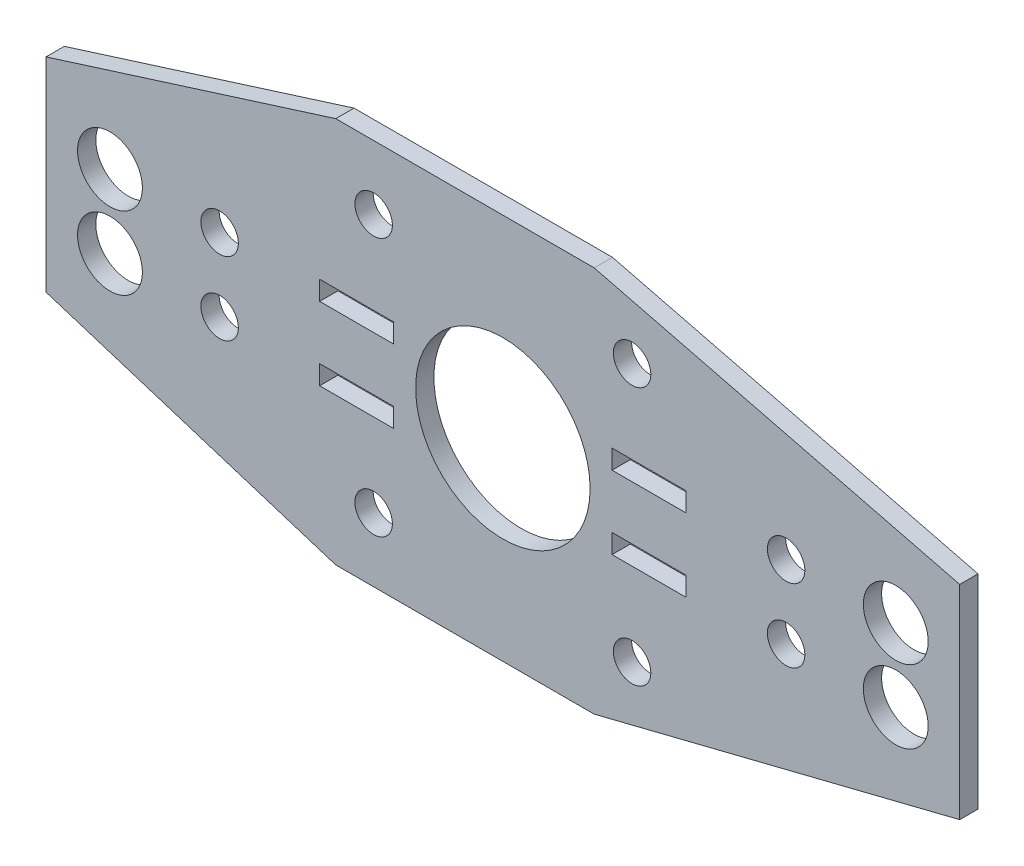
SolidWorks part; units mm, degrees
ref_plane "前视基准面" through (0, 0, 0) normal (0, 0, 1) x (1, 0, 0)
ref_plane "上视基准面" through (0, 0, 0) normal (0, 1, 0) x (1, 0, 0)
ref_plane "右视基准面" through (0, 0, 0) normal (1, 0, 0) x (0, 0, -1)
sketch "草图1" plane through (0, 0, 0) normal (0, 0, 1) x (1, 0, 0)
  line L0 (0, 0) -> (0, -8) construction
  line L1 (0, 0) -> (15, 0)
  line L2 (0, 0) -> (62, 0) construction
  line L3 (19.05, -1.05) -> (10.95, -1.05)
  line L4 (19.05, -1.05) -> (19.05, 1.05)
  line L5 (19.05, 1.05) -> (10.95, 1.05)
  line L6 (10.95, -1.05) -> (10.95, 1.05)
  line L7 (19.05, -1.05) -> (10.95, 1.05) construction
  line L8 (19.05, 1.05) -> (10.95, -1.05) construction
  line L9 (31, 0) -> (31, -4) construction
  line L10 (42.95, -1.05) -> (51.05, -1.05)
  line L11 (42.95, -1.05) -> (42.95, 1.05)
  line L12 (51.05, -1.05) -> (51.05, 1.05)
  line L13 (42.95, 1.05) -> (51.05, 1.05)
  line L14 (0, -4) -> (2.5207, -4) construction
  line L15 (51.05, -6.95) -> (51.05, -9.05)
  line L16 (42.95, -6.95) -> (42.95, -9.05)
  line L17 (42.95, -9.05) -> (51.05, -9.05)
  line L18 (42.95, -6.95) -> (51.05, -6.95)
  line L19 (19.05, -6.95) -> (19.05, -9.05)
  line L20 (10.95, -6.95) -> (10.95, -9.05)
  line L21 (19.05, -6.95) -> (10.95, -6.95)
  line L22 (19.05, -9.05) -> (10.95, -9.05)
  line L23 (31, -4) -> (31, 30.555) construction
  line L24 (81, -15.1497) -> (-19, -15.1497) construction
  line L25 (81, -15.1497) -> (81, 7.1497)
  line L26 (81, 7.1497) -> (-19, 7.1497) construction
  line L27 (-19, -15.1497) -> (-19, 7.1497)
  line L28 (81, -15.1497) -> (-19, 7.1497) construction
  line L29 (81, 7.1497) -> (-19, -15.1497) construction
  line L30 (31, -4) -> (54.6995, 19.6995) construction
  line L31 (-19, 7.1497) -> (12.7087, 17.1497)
  line L32 (12.7087, 17.1497) -> (40.993, 17.1497)
  line L33 (40.993, 17.1497) -> (81, 7.1497)
  line L34 (31, -4) -> (84.8449, -4) construction
  line L35 (12.7087, -25.1497) -> (40.993, -25.1497)
  line L36 (40.993, -25.1497) -> (81, -15.1497)
  line L37 (-19, -15.1497) -> (12.7087, -25.1497)
  line L38 (62, 0) -> (74, 0) construction
  circle A0 centre (0, 0) radius 2.05
  circle A1 centre (62, 0) radius 2.05
  circle A2 centre (62, -8) radius 2.05
  circle A3 centre (0, -8) radius 2.05
  circle A5 centre (31, -4) radius 20 construction
  circle A6 centre (45.1421, 10.1421) radius 2.05
  circle A7 centre (45.1421, -18.1421) radius 2.05
  circle A8 centre (16.8579, -18.1421) radius 2.05
  circle A9 centre (16.8579, 10.1421) radius 2.05
  circle A10 centre (74, 0) radius 3.55
  circle A11 centre (74, -8) radius 3.55
  circle A12 centre (-12, -8) radius 3.55
  circle A13 centre (-12, 0) radius 3.55
  circle A14 centre (31, -4) radius 9.55
  dimension "D2" = 4.1
  dimension "D8" = 4
  dimension "D10" = 12
  dimension "D12" = 19.1
  dimension "D1" = 8
  dimension "D3" = 15
  dimension "D4" = 8.1
  dimension "D5" = 2.1
  dimension "D6" = 62
  dimension "D7" = 45
  dimension "D9" = 10
  dimension "D11" = 100
extrude "凸台-拉伸1" add sketch "草图1" along normal blind 2
